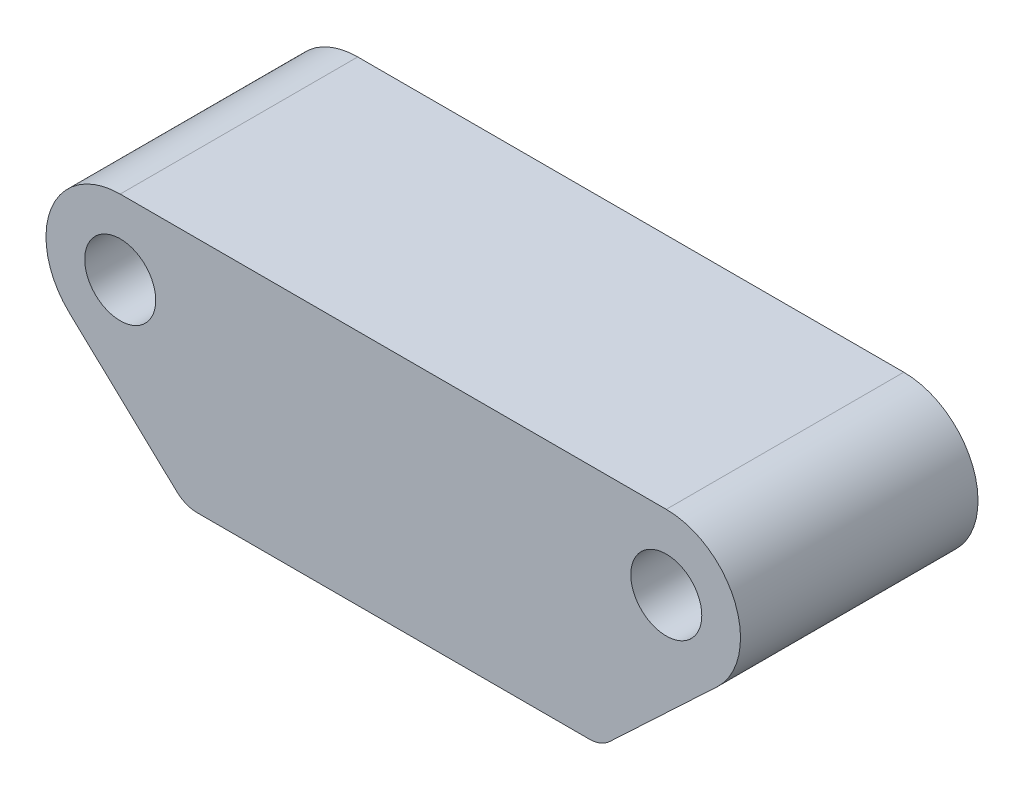
SolidWorks part; units mm, degrees
ref_plane "Front Plane" through (0, 0, 0) normal (0, 0, 1) x (1, 0, 0)
ref_plane "Top Plane" through (0, 0, 0) normal (0, 1, 0) x (1, 0, 0)
ref_plane "Right Plane" through (0, 0, 0) normal (1, 0, 0) x (0, 0, -1)
sketch "Sketch1" plane through (0, 0, 0) normal (0, 0, 1) x (1, 0, 0)
  line L0 (-17.3187, -0.5088) -> (-11.1125, -6.35)
  line L1 (-12.7, 6.35) -> (12.7, 6.35)
  line L3 (-11.1125, -6.35) -> (11.1125, -6.35)
  line L4 (12.7, 6.35) -> (12.7, -4.8559) construction
  line L5 (-12.7, 6.35) -> (12.7, -6.35) construction
  line L6 (-12.7, -6.35) -> (12.7, 6.35) construction
  line L7 (-14.5987, 6.35) -> (-12.7, 6.35)
  line L8 (-12.7, 6.35) -> (-12.7, -4.8559) construction
  line L9 (0, 6.35) -> (0, -6.35) construction
  line L10 (17.3187, -0.5088) -> (11.1125, -6.35)
  line L11 (14.5987, 6.35) -> (12.7, 6.35)
  arc A0 (-14.5987, 6.35) -> (-17.3187, -0.5088) centre (-14.5987, 2.3813) ccw
  arc A1 (14.5987, 6.35) -> (17.3187, -0.5088) centre (14.5987, 2.3813) cw
  circle A2 centre (-14.5987, 2.3813) radius 1.8986
  point P0 (0, 0)
  dimension "D3" = 7.9375
  dimension "D5" = 3.7973
  dimension "D1" = 12.7
  dimension "D2" = 25.4
  dimension "D4" = 1.5875
extrude "Boss-Extrude1" add sketch "Sketch1" along normal blind 12.7
fillet "Fillet1" radius 1.5875 2 edges at (11.1125, -6.35, 6.35) (-11.1125, -6.35, 6.35)
hole_wizard "#6 Clearance Hole1" positions "Sketch2" profile "Sketch3" hole size "#6" standard "ANSI Inch" end condition through all
sketch "Sketch2" plane through (0, 0, 12.7) normal (0, 0, 1) x (1, 0, 0)
  point P0 (-14.5987, 2.3813)
  point P3 (14.5987, 2.3813)
sketch "Sketch3" plane through (-14.5987, 2.3813, 12.7) normal (1, 0, 0) x (0, -1, 0)
  line L0 (0, 0) -> (0, 12.7)
  line L1 (0, 12.7) -> (1.8986, 12.7)
  line L2 (1.8986, 12.7) -> (1.8986, 0)
  line L5 (1.8986, 0) -> (0, 0)
  line L11 (0, -6.35) -> (0, 107.95) construction
  dimension "Thru Hole Dia." = 3.7973
  dimension "Thru Hole Depth" = 12.7
